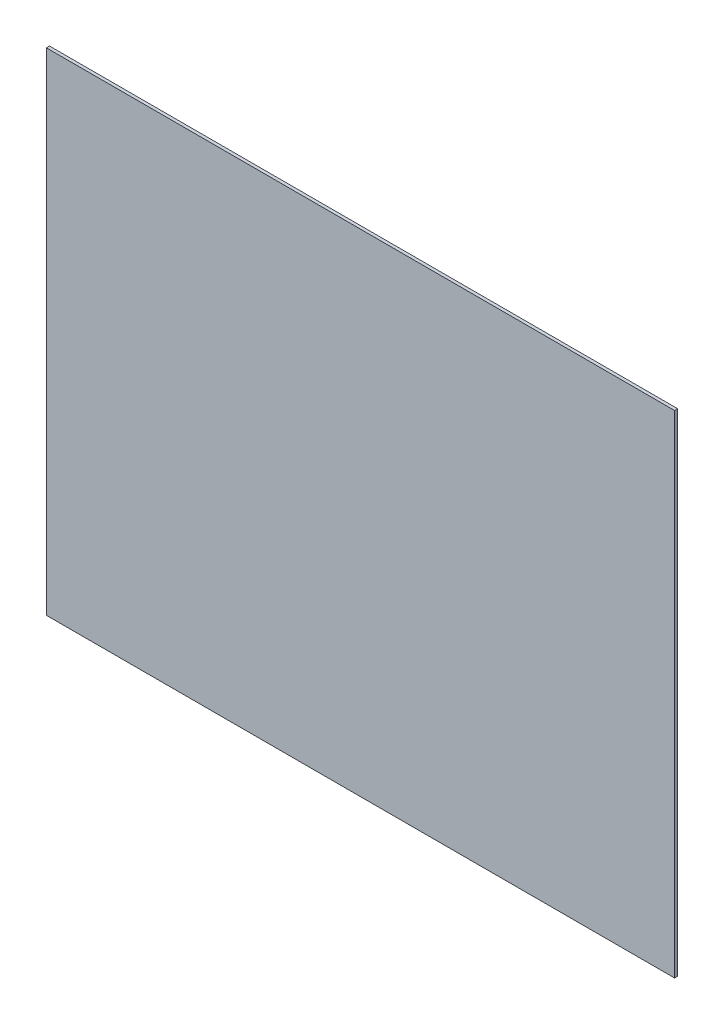
SolidWorks part; units mm, degrees
material "Custom Plastic"
ref_plane "X-Y Datum" through (0, 0, 0) normal (0, 0, 1) x (1, 0, 0)
ref_plane "X-Z Datum" through (0, 0, 0) normal (0, 1, 0) x (1, 0, 0)
ref_plane "Y-Z Datum" through (0, 0, 0) normal (1, 0, 0) x (0, 0, -1)
sketch "Sketch1" plane through (0, 0, 0) normal (0, 0, 1) x (1, 0, 0)
  line L1 (-232.537, 181.95) -> (232.537, 181.95)
  line L2 (-232.537, 181.95) -> (-232.537, -181.95)
  line L3 (-232.537, -181.95) -> (232.537, -181.95)
  line L4 (232.537, 181.95) -> (232.537, -181.95)
  line L5 (-232.537, 181.95) -> (232.537, -181.95) construction
  line L6 (-232.537, -181.95) -> (232.537, 181.95) construction
  point P0 (0, 0)
  dimension "D1" = 363.9
  dimension "D2" = 465.074
extrude "Boss-Extrude1" add sketch "Sketch1" along normal blind 2.286
